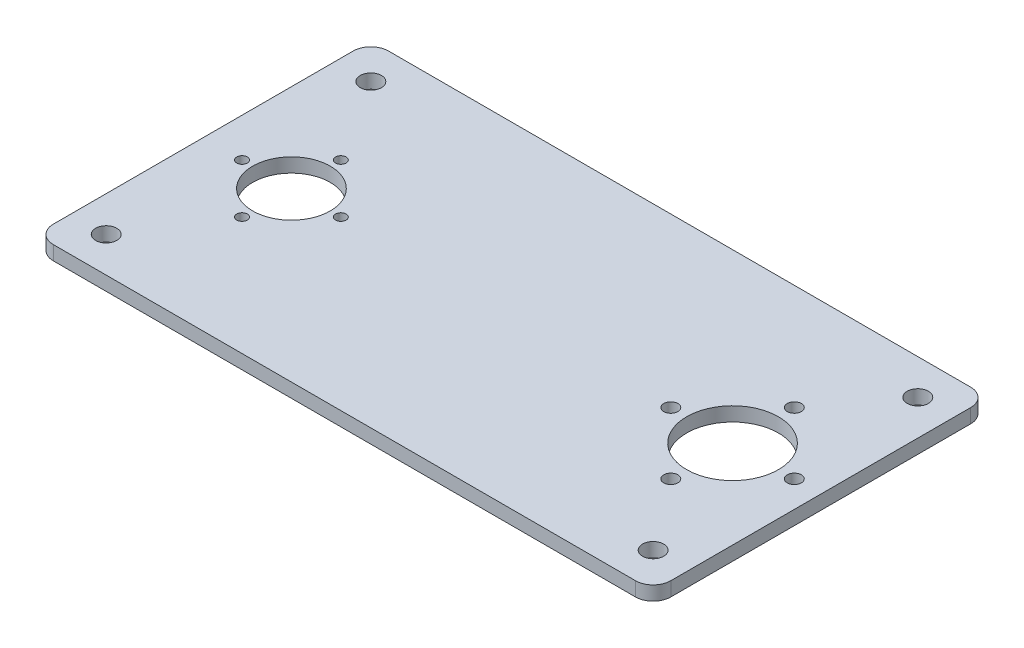
SolidWorks part; units mm, degrees
ref_plane "前视基准面" through (0, 0, 0) normal (0, 0, 1) x (1, 0, 0)
ref_plane "上视基准面" through (0, 0, 0) normal (0, 1, 0) x (1, 0, 0)
ref_plane "右视基准面" through (0, 0, 0) normal (1, 0, 0) x (0, 0, -1)
sketch "草图1" plane through (0, 0, 0) normal (0, 1, 0) x (1, 0, 0)
  line L0 (0, 0) -> (-125, 0) construction
  line L1 (-140, 37.5) -> (-140, -37.5) construction
  line L2 (-150, 47.5) -> (25, 47.5)
  line L3 (-150, 47.5) -> (-150, -47.5)
  line L4 (-150, -47.5) -> (25, -47.5)
  line L5 (25, 47.5) -> (25, -47.5)
  line L6 (-140, -37.5) -> (15, -37.5) construction
  line L7 (15, 37.5) -> (15, -37.5) construction
  line L8 (-140, 37.5) -> (15, 37.5) construction
  circle A0 centre (0, 0) radius 13
  circle A1 centre (0, 0) radius 17.5 construction
  circle A2 centre (-125, 0) radius 11
  circle A3 centre (-125, 0) radius 14 construction
  circle A4 centre (0, 17.5) radius 2
  circle A5 centre (17.5, 0) radius 2
  circle A6 centre (0, -17.5) radius 2
  circle A7 centre (-17.5, 0) radius 2
  circle A12 centre (-140, 37.5) radius 3
  circle A13 centre (-140, -37.5) radius 3
  circle A14 centre (15, 37.5) radius 3
  circle A15 centre (15, -37.5) radius 3
  circle A16 centre (-125, 14) radius 1.5
  circle A29 centre (-111, 0) radius 1.5
  circle A30 centre (-125, -14) radius 1.5
  circle A31 centre (-139, 0) radius 1.5
  point P22 (0, 0)
  point P39 (-125, 0)
  dimension "D1" = 4
  dimension "D2" = 155
  dimension "D4" = 4
  dimension "D5" = 25
  dimension "D7" = 95
  dimension "D6" = 175
  dimension "D8" = 47.5
  dimension "D3" = 10
extrude "凸台-拉伸1" add sketch "草图1" along normal blind 4
fillet "圆角1" radius 5 4 edges at (25, 2, 47.5) (25, 2, -47.5) (-150, 2, 47.5) (-150, 2, -47.5)
